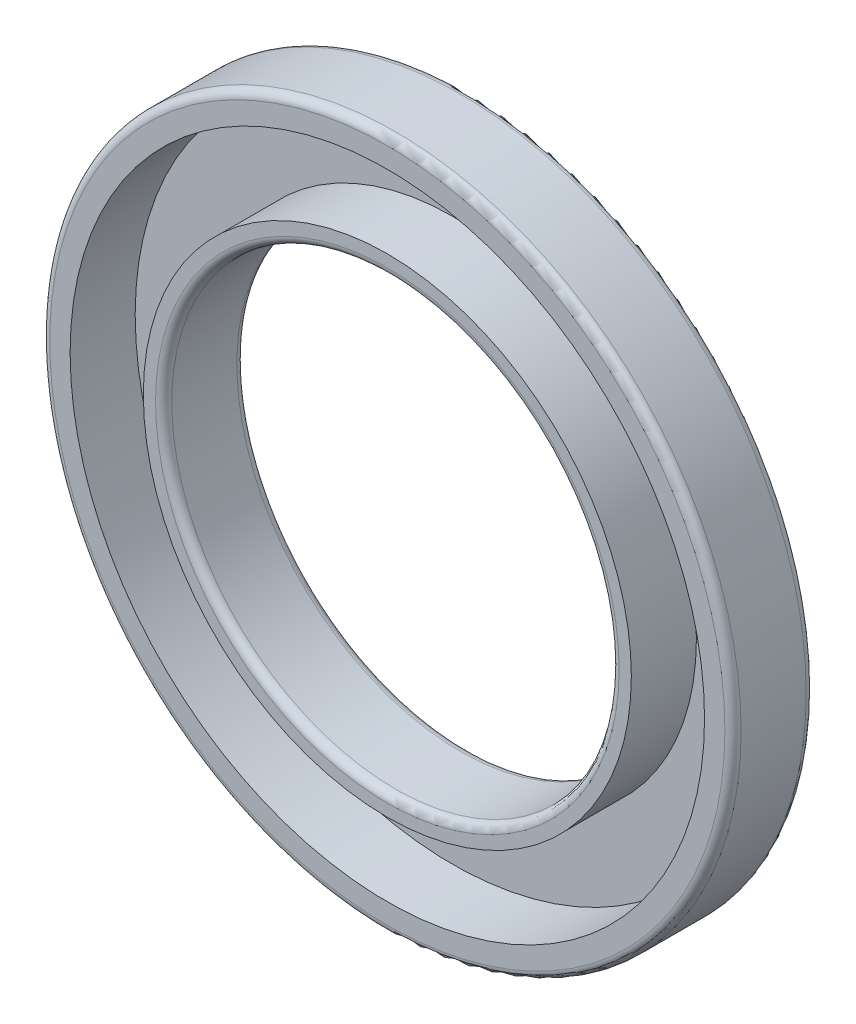
SolidWorks part; units mm, degrees
ref_plane "Front Plane" through (0, 0, 0) normal (0, 0, 1) x (1, 0, 0)
ref_plane "Top Plane" through (0, 0, 0) normal (0, 1, 0) x (1, 0, 0)
ref_plane "Right Plane" through (0, 0, 0) normal (1, 0, 0) x (0, 0, -1)
sketch "Sketch1" plane through (0, 0, 0) normal (0, 0, 1) x (1, 0, 0)
  circle A0 centre (0, 0) radius 42.5
  circle A1 centre (0, 0) radius 27.5
  dimension "D1" = 55
  dimension "D2" = 85
extrude "Boss-Extrude1" add sketch "Sketch1" along normal blind 10
sketch "Sketch2" plane through (0, 0, 10) normal (0, 0, 1) x (1, 0, 0)
  circle A0 centre (0, 0) radius 30
  circle A1 centre (0, 0) radius 39
  dimension "D1" = 60
  dimension "D2" = 78
extrude "Cut-Extrude1" cut sketch "Sketch2" against normal blind 8
fillet "Fillet1" radius 1 4 edges at (27.5, 0, 0) (27.5, 0, 10) (42.5, 0, 10) (42.5, 0, 0)
